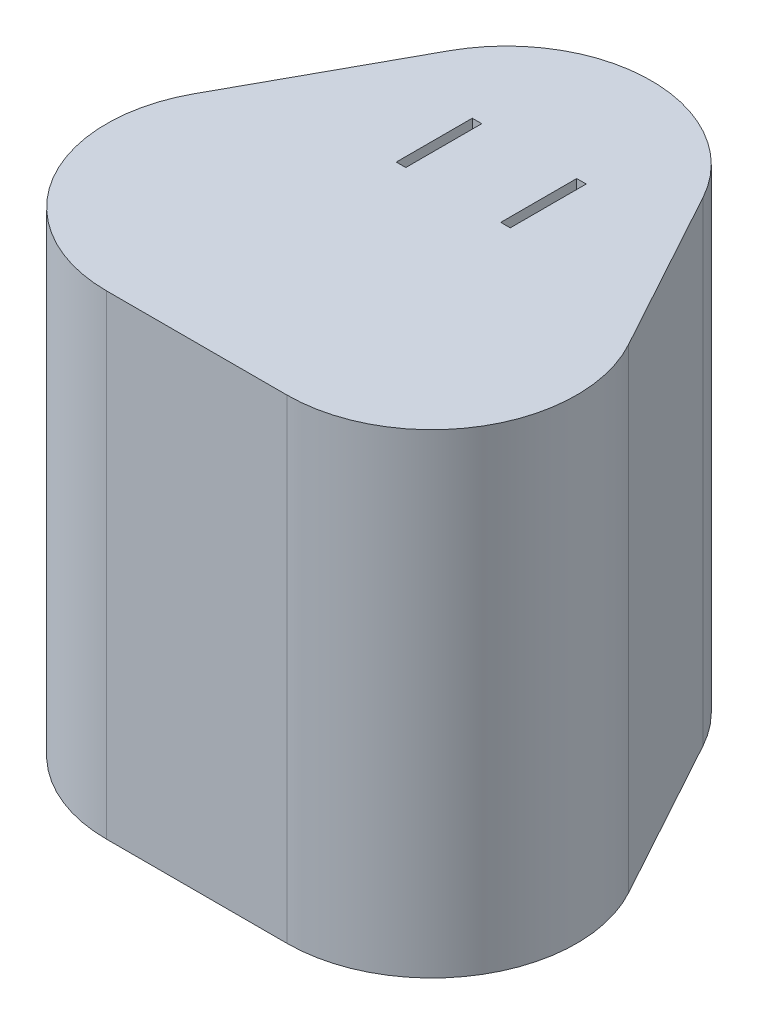
SolidWorks part; units mm, degrees
ref_plane "Plano frontal" through (0, 0, 0) normal (0, 0, 1) x (1, 0, 0)
ref_plane "Plano superior" through (0, 0, 0) normal (0, 1, 0) x (1, 0, 0)
ref_plane "Plano direito" through (0, 0, 0) normal (1, 0, 0) x (0, 0, -1)
sketch "Esboço1" plane through (0, 0, 0) normal (0, 1, 0) x (1, 0, 0)
  line L7 (-13.3761, 16.0541) -> (-22.8761, -1.2959)
  line L8 (13.3761, 16.0541) -> (22.8761, -1.2959)
  line L9 (-9.5, -23.87) -> (9.5, -23.87)
  arc A2 (-22.8761, -1.2959) -> (-9.5, -23.87) centre (-9.5, -8.62) ccw
  arc A6 (13.3761, 16.0541) -> (-13.3761, 16.0541) centre (0, 8.73) ccw
  arc A7 (9.5, -23.87) -> (22.8761, -1.2959) centre (9.5, -8.62) ccw
extrude "Ressalto-extrusão2" add sketch "Esboço1" along normal blind 50
sketch "Esboço3" plane through (0, 0, 0) normal (0, -1, 0) x (1, 0, 0)
  line L0 (-9.5, 19.37) -> (9.5, 19.37)
  line L1 (-18.9291, 3.4571) -> (-9.4291, -13.8929)
  line L2 (18.9291, 3.4571) -> (9.4291, -13.8929)
  arc A3 (-9.5, 19.37) -> (-18.9291, 3.4571) centre (-9.5, 8.62) ccw
  arc A4 (18.9291, 3.4571) -> (9.5, 19.37) centre (9.5, 8.62) ccw
  arc A5 (-9.4291, -13.8929) -> (9.4291, -13.8929) centre (0, -8.73) ccw
extrude "Corte-extrusão1" cut sketch "Esboço3" against normal blind 38
sketch "Esboço4" plane through (0, 0, 0) normal (0, -1, 0) x (1, 0, 0)
  line L2 (0, 3.37) -> (18.8814, 3.37)
  line L3 (0, 3.37) -> (-18.8814, 3.37)
  line L4 (-9.4291, -13.8929) -> (-18.8814, 3.37)
  line L5 (9.4291, -13.8929) -> (18.8814, 3.37)
  arc A2 (-9.4291, -13.8929) -> (9.4291, -13.8929) centre (0, -8.73) ccw
extrude "Corte-extrusão3" cut sketch "Esboço4" against normal blind 47
sketch "Esboço5" plane through (0, 0, 0) normal (0, -1, 0) x (-1, 0, 0)
  line L2 (-5, 11.13) -> (-5, 3.13)
  line L3 (-5, 3.13) -> (-6, 3.13)
  line L4 (-6, 3.13) -> (-6, 11.13)
  line L5 (-6, 11.13) -> (-5, 11.13)
  line L7 (5, 11.13) -> (6, 11.13)
  line L8 (6, 11.13) -> (6, 3.13)
  line L9 (6, 3.13) -> (5, 3.13)
  line L10 (5, 3.13) -> (5, 11.13)
extrude "Corte-extrusão4" cut sketch "Esboço5" against normal through all
sketch "Esboço6" plane through (0, 0, 0) normal (0, -1, 0) x (1, 0, 0)
  line L0 (-13.7742, -10.63) -> (13.7809, -10.63)
  line L2 (-13.7742, -10.63) -> (-19.2344, -0.63)
  line L3 (13.7809, -10.63) -> (19.2564, -0.63)
  line L4 (2.7928, -0.63) -> (-19.2344, -0.63)
  line L5 (2.7928, -0.63) -> (19.2564, -0.63)
extrude "Corte-extrusão5" cut sketch "Esboço6" against normal blind 7
sketch "Esboço7" plane through (0, 0, 0) normal (0, -1, 0) x (1, 0, 0)
  line L2 (0, -12.48) -> (13, -12.48)
  line L3 (13, -12.48) -> (13, -8.48)
  line L4 (13, -8.48) -> (-13, -8.48)
  line L5 (0, -12.48) -> (-13, -12.48)
  line L6 (-13, -12.48) -> (-13, -8.48)
extrude "Corte-extrusão6" cut sketch "Esboço7" against normal blind 47
